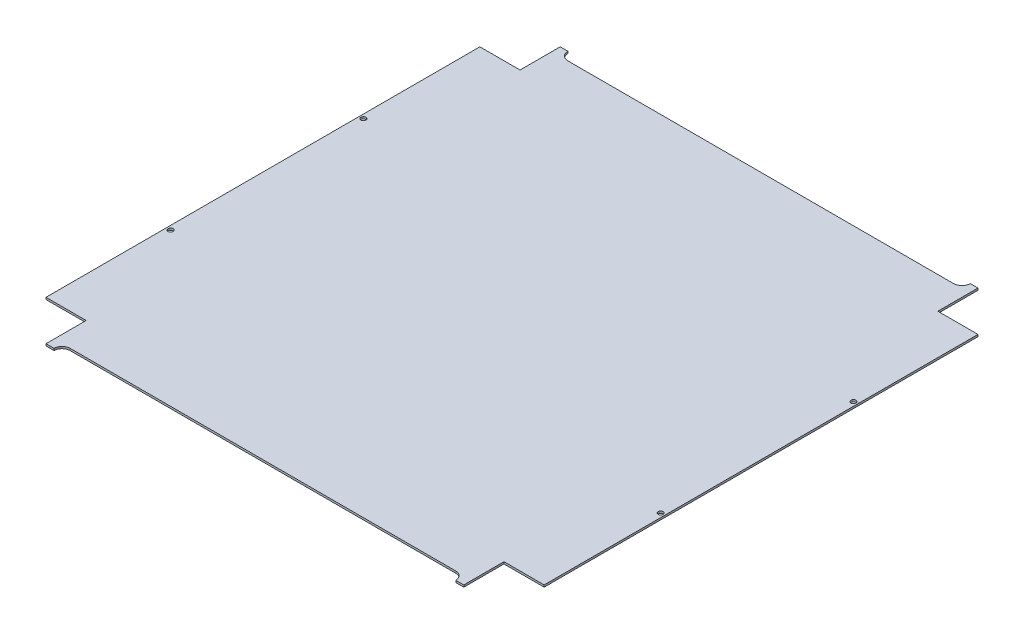
SolidWorks part; units mm, degrees
material "PC High Viscosity"
ref_plane "Front Plane" through (0, 0, 0) normal (0, 0, 1) x (1, 0, 0)
ref_plane "Top Plane" through (0, 0, 0) normal (0, 1, 0) x (1, 0, 0)
ref_plane "Right Plane" through (0, 0, 0) normal (1, 0, 0) x (0, 0, -1)
sketch "Sketch1" plane through (0, 0, 0) normal (0, 1, 0) x (1, 0, 0)
  line L0 (-154.1487, -201.3949) -> (150.6513, -201.3949) construction
  line L1 (-198.5987, 205.0051) -> (195.1013, 205.0051)
  line L2 (-198.5987, 205.0051) -> (-198.5987, -201.3949)
  line L3 (-198.5987, -201.3949) -> (195.1013, -201.3949)
  line L4 (195.1013, 205.0051) -> (195.1013, -201.3949)
  line L5 (-198.5987, 205.0051) -> (195.1013, -201.3949) construction
  line L7 (-154.1487, -195.0449) -> (150.6513, -195.0449)
  line L8 (-154.1487, -207.7449) -> (150.6513, -207.7449)
  line L9 (195.1013, 205.0051) -> (163.3513, 205.0051)
  line L12 (195.1013, 205.0051) -> (195.1013, 173.2551)
  line L13 (195.1013, 173.2551) -> (163.3513, 173.2551)
  line L14 (163.3513, 205.0051) -> (163.3513, 173.2551)
  line L15 (-198.5987, 205.0051) -> (-166.8487, 205.0051)
  line L21 (-198.5987, 205.0051) -> (-198.5987, 173.2551)
  line L22 (-154.1487, 205.0051) -> (150.6513, 205.0051) construction
  line L23 (-154.1487, 211.6124) -> (150.6513, 211.6124)
  line L24 (-154.1487, 198.3979) -> (150.6513, 198.3979)
  line L25 (-198.5987, 173.2551) -> (-166.8487, 173.2551)
  line L26 (-166.8487, 205.0051) -> (-166.8487, 173.2551)
  line L27 (-198.5987, -201.3949) -> (-166.8487, -201.3949)
  line L28 (-198.5987, -201.3949) -> (-198.5987, -169.6449)
  line L29 (-198.5987, -169.6449) -> (-166.8487, -169.6449)
  line L30 (-166.8487, -201.3949) -> (-166.8487, -169.6449)
  line L31 (195.1013, -201.3949) -> (163.3513, -201.3949)
  line L32 (195.1013, -201.3949) -> (195.1013, -169.6449)
  line L33 (195.1013, -169.6449) -> (163.3513, -169.6449)
  line L34 (163.3513, -201.3949) -> (163.3513, -169.6449)
  arc A0 (-154.1487, -195.0449) -> (-154.1487, -207.7449) centre (-154.1487, -201.3949) ccw
  arc A1 (150.6513, -207.7449) -> (150.6513, -195.0449) centre (150.6513, -201.3949) ccw
  arc A30 (-154.1487, 211.6124) -> (-154.1487, 198.3979) centre (-154.1487, 205.0051) ccw
  arc A31 (150.6513, 198.3979) -> (150.6513, 211.6124) centre (150.6513, 205.0051) ccw
  point P0 (0, 0)
  point P8 (-1.7487, -201.3949)
  point P13 (-1.7487, -201.3949)
  point P14 (-1.7487, -201.3949)
  point P27 (-195.4237, -74.3949)
  point P28 (191.9263, 78.0051)
  point P29 (191.9263, -74.3949)
  point P30 (-195.4237, 78.0051)
  point P85 (-1.7487, 205.0051)
  dimension "D4" = 6.35
  dimension "D9" = 3.175
  dimension "D11" = 152.4
  dimension "D6" = 44.45
  dimension "D24" = 31.75
  dimension "D1" = 393.7
  dimension "D2" = 406.4
  dimension "D3" = 44.45
  dimension "D5" = 0
  dimension "D7" = 152.4
  dimension "D8" = 127
  dimension "D10" = 3.175
  dimension "D12" = 127
  dimension "D13" = 3.175
  dimension "D14" = 3.175
  dimension "D22" = 44.45
  dimension "D23" = 0
  dimension "D25" = 31.75
  dimension "D26" = 31.75
  dimension "D27" = 31.75
  dimension "D28" = 31.75
  dimension "D29" = 31.75
  dimension "D30" = 31.75
extrude "Boss-Extrude1" add sketch "Sketch1" along normal blind 1.5875
hole_wizard "5/32 (0.15625) Diameter Hole1" positions "Sketch4" profile "Sketch5" hole size "5/32" standard "ANSI Inch" end condition through all
sketch "Sketch4" plane through (0, 1.5875, 0) normal (0, 1, 0) x (1, 0, 0)
  point P0 (-195.4237, 78.0051)
  point P3 (-195.4237, -74.3949)
  point P6 (191.9263, -74.3949)
  point P9 (191.9263, 78.0051)
sketch "Sketch5" plane through (-195.4237, 1.5875, -78.0051) normal (1, 0, 0) x (0, 0, 1)
  line L0 (0, 0) -> (0, 1.5875)
  line L1 (0, 1.5875) -> (1.9844, 1.5875)
  line L2 (1.9844, 1.5875) -> (1.9844, 0)
  line L5 (1.9844, 0) -> (0, 0)
  line L11 (0, -6.35) -> (0, 107.95) construction
  dimension "Thru Hole Dia." = 3.9688
  dimension "Thru Hole Depth" = 1.5875
